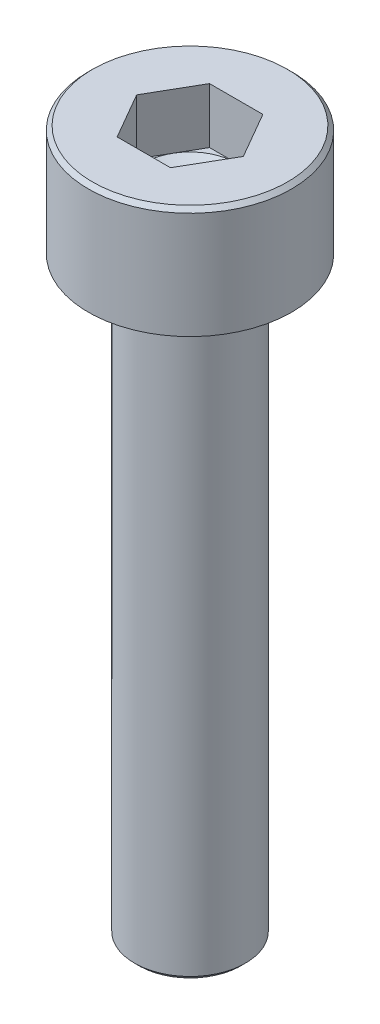
SolidWorks part; units mm, degrees
ref_plane "前视基准面" through (0, 0, 0) normal (0, 0, 1) x (1, 0, 0)
ref_plane "上视基准面" through (0, 0, 0) normal (0, 1, 0) x (1, 0, 0)
ref_plane "右视基准面" through (0, 0, 0) normal (1, 0, 0) x (0, 0, -1)
sketch "草图1" plane through (0, 0, 0) normal (0, 0, 1) x (1, 0, 0)
  line L0 (0, 0) -> (0, -19) construction
  line L1 (-1.5, -3) -> (-2.75, -3)
  line L2 (-1.5, -3) -> (-1.5, -19)
  line L3 (-1.5, -19) -> (0, -19)
  line L6 (-1.25, 0) -> (-1.25, -1.5)
  line L7 (-1.25, -1.5) -> (0, -2.2217)
  line L11 (-1.5, -3) -> (-2.75, -3)
  line L12 (-2.75, -3) -> (-2.75, 0)
  line L13 (-2.75, 0) -> (0, 0)
  point P0 (-0.6, -19)
  dimension "D1" = 60
  dimension "M" = 3
  dimension "L" = 16
  dimension "t" = 1.5
  dimension "B" = 2.5
  dimension "E" = 3
  dimension "A" = 5.5
  dimension "(d)" = 1.2
sketch "草图2" plane through (0, 0, 0) normal (0, 0, 1) x (1, 0, 0)
  line L0 (-1.25, 0) -> (-1.25, -1.5) construction
  line L1 (-1.25, -1.5) -> (0, -2.2217) construction
  line L3 (-1.5, -3) -> (-1.5, -19) construction
  line L4 (-1.5, -3) -> (-2.75, -3) construction
  line L7 (-1.25, 0) -> (-1.25, -1.5)
  line L8 (-1.25, -1.5) -> (0, -2.2217)
  line L9 (-2.75, -3) -> (-2.75, 0) construction
  line L10 (-1.5, -3) -> (-1.5, -19)
  line L14 (0, -2.2217) -> (0, -19)
  line L16 (-1.5, -19) -> (0, -19) construction
  line L19 (-1.5, -19) -> (0, -19)
  line L20 (-2.75, 0) -> (0, 0) construction
  line L21 (-1.5, -3) -> (-2.75, -3)
  line L22 (-2.75, -3) -> (-2.75, 0)
  line L23 (-2.75, 0) -> (-1.25, 0)
revolve "旋转1" add sketch "草图2" angle 360 mid plane about L14
cosmetic thread "装饰螺纹线1"
chamfer "倒角1" distance 0.12 angle 45 1 edges at (-1.5, -19, 0)
chamfer "倒角2" distance 0.11 angle 45 1 edges at (-2.75, 0, 0)
sketch "草图3" plane through (0, 0, 0) normal (0, 1, 0) x (-1, 0, 0)
  line L1 (-0.7217, 1.25) -> (-1.4434, 0)
  line L2 (-1.4434, 0) -> (-0.7217, -1.25)
  line L3 (-0.7217, -1.25) -> (0.7217, -1.25)
  line L4 (0.7217, -1.25) -> (1.4434, 0)
  line L5 (1.4434, 0) -> (0.7217, 1.25)
  line L6 (0.7217, 1.25) -> (-0.7217, 1.25)
  circle A0 centre (0, 0) radius 1.25 construction
extrude "切除-拉伸1" cut sketch "草图3" against normal up to vertex (1.5 mm away) up to point (-1.25, -1.5, 0)
sketch "草图4" plane through (0, -19, 0) normal (0, -1, 0) x (1, 0, 0)
  circle A0 centre (0, 0) radius 0.6
extrude "切除-拉伸2" cut sketch "草图4" against normal up to vertex up to point (0, 0, 0)
